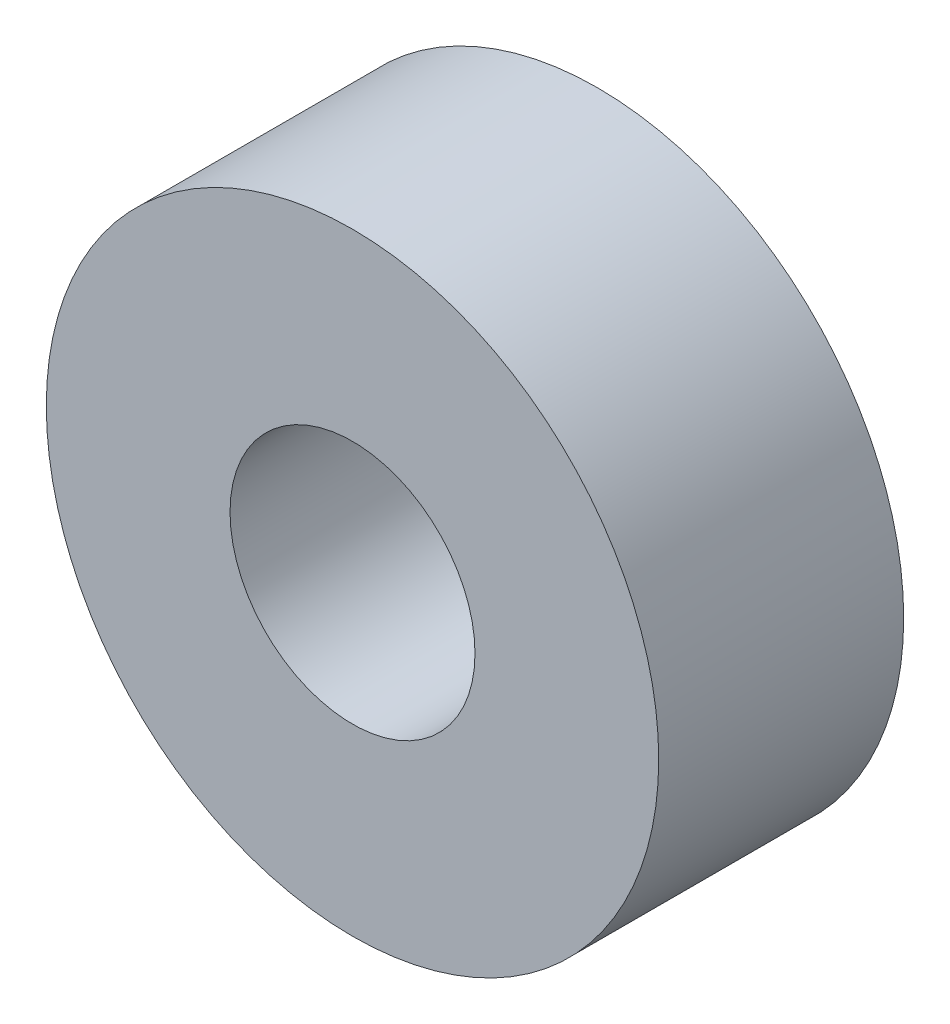
SolidWorks part; units mm, degrees
other "Bearing_5-2-2"
material "1.5714 (16NiCr4)"
ref_plane "Front" through (0, 0, 0) normal (0, 0, 1) x (1, 0, 0)
ref_plane "Top" through (0, 0, 0) normal (0, 1, 0) x (1, 0, 0)
ref_plane "Right" through (0, 0, 0) normal (1, 0, 0) x (0, 0, -1)
sketch "BearingSke" plane through (0, 0, 0) normal (0, 0, 1) x (1, 0, 0)
  circle A0 centre (0, 0) radius 2.5
  circle A1 centre (0, 0) radius 1
  dimension "D1" = 5
  dimension "D2" = 2
extrude "Bearing" add sketch "BearingSke" along normal blind 2
